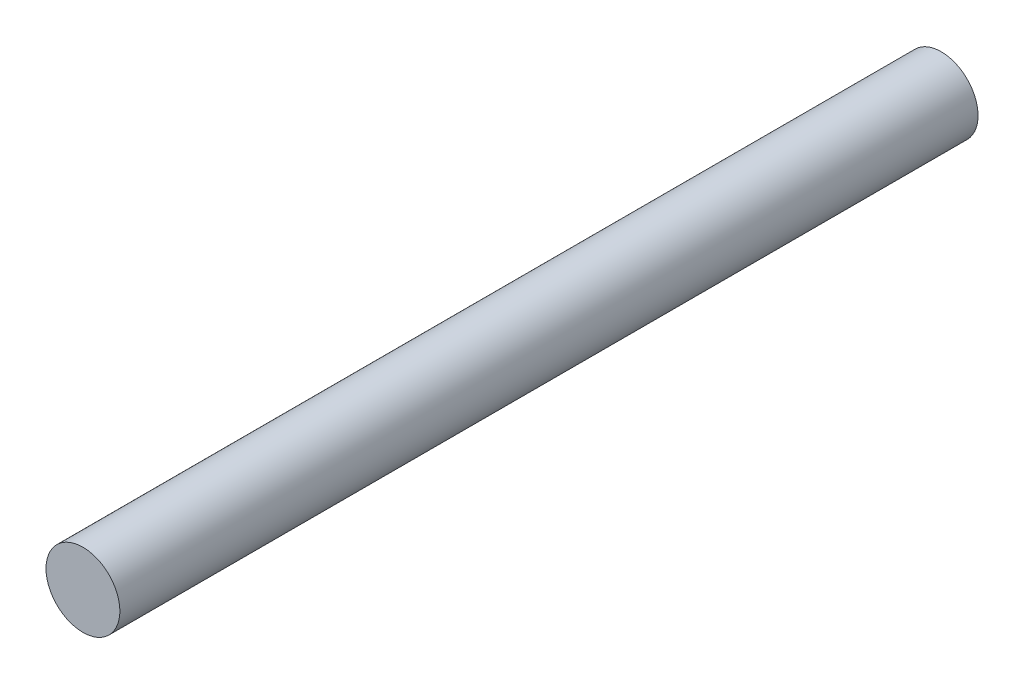
SolidWorks part; units mm, degrees
ref_plane "Front Plane" through (0, 0, 0) normal (0, 0, 1) x (1, 0, 0)
ref_plane "Top Plane" through (0, 0, 0) normal (0, 1, 0) x (1, 0, 0)
ref_plane "Right Plane" through (0, 0, 0) normal (1, 0, 0) x (0, 0, -1)
sketch "Sketch1" plane through (0, 0, 0) normal (0, 0, 1) x (1, 0, 0)
  circle A0 centre (0, 0) radius 4
  dimension "D1" = 8
extrude "Boss-Extrude1" add sketch "Sketch1" along normal blind 93
